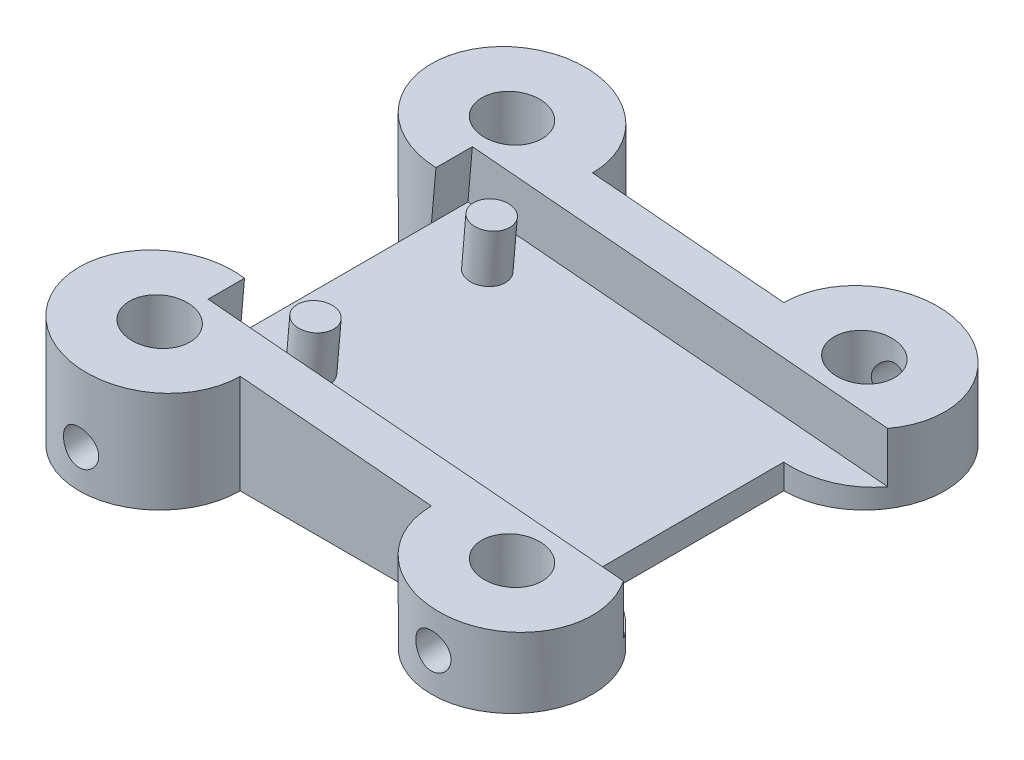
SolidWorks part; units mm, degrees
ref_plane "Front Plane" through (0, 0, 0) normal (0, 0, 1) x (1, 0, 0)
ref_plane "Top Plane" through (0, 0, 0) normal (0, 1, 0) x (1, 0, 0)
ref_plane "Right Plane" through (0, 0, 0) normal (1, 0, 0) x (0, 0, -1)
sketch "Sketch1" plane through (0, 0, 0) normal (0, 1, 0) x (1, 0, 0)
  line L0 (14, 28) -> (14, 0) construction
  line L1 (0, 0) -> (28, 0)
  line L2 (0, 0) -> (0, 28)
  line L3 (0, 28) -> (28, 28)
  line L4 (28, 0) -> (28, 28)
  line L5 (0, 14) -> (28, 14) construction
  point P9 (14, 14)
  dimension "D1" = 28
extrude "Boss-Extrude1" add sketch "Sketch1" along normal blind 8.4497
sketch "Sketch2" plane through (0, 0, 0) normal (0, 0, 1) x (1, 0, 0)
  line L0 (0, 8.4497) -> (28, 6)
  line L1 (0, 8.4497) -> (28, 8.4497) construction
  line L2 (28, 8.4497) -> (28, 0) construction
  line L3 (0, 8.4497) -> (28, 8.4497)
  line L4 (28, 8.4497) -> (28, 6)
  dimension "D2" = 6
  dimension "D3" = 5
extrude "Cut-Extrude1" cut sketch "Sketch2" against normal through all
sketch "Sketch3" plane through (0.7336, 8.3855, 0) normal (0.0872, 0.9962, 0) x (0.9962, -0.0872, 0)
  line L0 (-0.7364, 28) -> (-0.7364, 0) construction
  line L1 (-0.7364, 3.5) -> (49.2636, 3.5)
  line L2 (-0.7364, 3.5) -> (-0.7364, 24.5)
  line L3 (-0.7364, 24.5) -> (49.2636, 24.5)
  line L4 (49.2636, 3.5) -> (49.2636, 24.5)
  point P9 (-0.7364, 14)
  point P10 (-0.7364, 14)
  dimension "D1" = 21
  dimension "D2" = 50
extrude "Cut-Extrude2" cut sketch "Sketch3" against normal blind 4
ref_plane "Plane1" through (0, 8.4497, 0) normal (0, 1, 0) x (1, 0, 0)
sketch "Sketch11" plane through (0.385, 4.4007, 0) normal (0.0872, 0.9962, 0) x (0.9962, -0.0872, 0)
  line L0 (27.7205, 24.5) -> (-0.3865, 24.5) construction
  line L1 (27.7205, 24.5) -> (27.7205, 3.5) construction
  line L2 (-0.3865, 3.5) -> (27.7205, 3.5) construction
  line L3 (27.7205, 24.5) -> (-0.3865, 24.5) construction
  line L4 (27.7205, 24.5) -> (27.7205, 3.5) construction
  line L5 (-0.3865, 3.5) -> (27.7205, 3.5) construction
  line L6 (13.667, 3) -> (13.667, 50003) construction
  line L7 (24.633, 14) -> (-49975.367, 14) construction
  circle A2 centre (4.667, 21) radius 1.45
  circle A3 centre (4.667, 7) radius 1.45
  point P6 (13.667, 3.5)
  point P9 (27.7205, 14)
  dimension "D4" = 2.9
  dimension "D5" = 9
  dimension "D6" = 7
extrude "Boss-Extrude2" add sketch "Sketch11" along normal blind 4
sketch "Sketch12" plane through (0, 8.4497, 0) normal (0, 1, 0) x (1, 0, 0)
  line L0 (0, 3.5) -> (0, 24.5) construction
  line L1 (0, 3.5) -> (28, 3.5) construction
  line L2 (0, 3.5) -> (0, 24.5) construction
  line L3 (0, 3.5) -> (28, 3.5) construction
  line L4 (0, 14) -> (50000, 14) construction
  line L5 (14, 4) -> (14, 50004) construction
  circle A0 centre (14, 14) radius 7
  point P7 (0, 14)
  point P10 (14, 3.5)
  dimension "D1" = 14
sketch "Sketch13" plane through (0, 0, 0) normal (0, -1, 0) x (1, 0, 0)
  line L0 (0, 0) -> (28, 0) construction
  line L1 (28, 0) -> (28, -28) construction
  line L2 (28, -28) -> (0, -28) construction
  line L3 (0, -28) -> (0, 0) construction
  line L4 (0, 0) -> (28, 0) construction
  line L5 (28, 0) -> (28, -28) construction
  line L6 (28, -28) -> (0, -28) construction
  line L7 (0, -28) -> (0, 0) construction
  line L8 (0, -14) -> (28, -14) construction
  line L9 (14, -28) -> (14, 0) construction
  circle A0 centre (0, 0) radius 2.4
  circle A1 centre (28, 0) radius 2.4
  circle A2 centre (28, -28) radius 2.4
  circle A3 centre (0, -28) radius 2.4
  dimension "D1" = 4.8
  dimension "D2" = 2
  dimension "D3" = 2
extrude "Cut-Extrude5" cut sketch "Sketch13" against normal through all
sketch "Sketch14" plane through (0, 0, 0) normal (0, -1, 0) x (1, 0, 0)
  line L0 (28, -3.5) -> (28, -2.4) construction
  line L1 (2.4, -28) -> (25.6, -28) construction
  line L2 (0, -3.5) -> (0, -24.5) construction
  circle A0 centre (0, 0) radius 2.4 construction
  circle A1 centre (0, 0) radius 2.4 construction
  circle A2 centre (0, 0) radius 6.4
  circle A3 centre (0, 0) radius 2.4
  circle A4 centre (28, 0) radius 2.4
  circle A5 centre (28, 0) radius 6.4
  circle A6 centre (28, -28) radius 2.4
  circle A7 centre (28, -28) radius 6.4
  circle A8 centre (0, -28) radius 2.4
  circle A9 centre (0, -28) radius 6.4
  dimension "D1" = 4
  dimension "D4" = 4.8
  dimension "D2" = 2
  dimension "D3" = 2
extrude "Boss-Extrude3" add sketch "Sketch14" against normal up to surface (8.4497 mm away)
sketch "Sketch15" plane through (0, 0, -28) normal (0, 0, -1) x (-1, 0, 0)
  line L0 (-21.6, 0) -> (-6.4, 0) construction
  line L1 (-21.9, 0) -> (-0.9, 0) construction
  line L4 (-14, 7.2248) -> (-14, 0) construction
  line L5 (-6.4, 7.8898) -> (-21.6, 6.5599) construction
  circle A0 centre (-28, 3) radius 1.4
  circle A1 centre (0, 3) radius 1.4
  point P4 (-28, 0)
  dimension "D1" = 2.8
  dimension "D2" = 3
extrude "Cut-Extrude6" cut sketch "Sketch15" along normal through all
sketch "Sketch16" plane through (0, 0, 0) normal (0, 0, 1) x (1, 0, 0)
  circle A0 centre (0, 3) radius 1.4 construction
  circle A1 centre (28, 3) radius 1.4 construction
  circle A2 centre (0, 3) radius 1.4
  circle A3 centre (28, 3) radius 1.4
extrude "Cut-Extrude7" cut sketch "Sketch16" along normal through all
sketch "Sketch18" plane through (0.7336, 8.3855, 0) normal (0.0872, 0.9962, 0) x (0.9962, -0.0872, 0)
  line L5 (-0.7364, 3.5) -> (27.157, 3.5) construction
  line L8 (4.6422, 3.5) -> (21.9919, 3.5) construction
  line L9 (4.6422, 3.5) -> (21.9919, 3.5) construction
  line L22 (4.9922, 24.5) -> (-0.3865, 24.5)
  line L37 (6.9919, 3.5) -> (36.9919, 3.5)
  line L38 (6.9919, 3.5) -> (6.9919, 24.5)
  line L39 (6.9919, 24.5) -> (36.9919, 24.5)
  line L40 (36.9919, 3.5) -> (36.9919, 24.5)
  line L42 (-0.3865, 24.5) -> (-0.3865, 21.6)
  line L46 (-0.3865, 6.4) -> (-0.3865, 3.5)
  line L47 (-0.3865, 3.5) -> (4.9922, 3.5)
  line L49 (4.6422, 24.5) -> (21.9919, 24.5) construction
  ellipse E1 centre (-0.3865, 28) end of major axis (6.038, 28) minor radius 6.4 (-0.3865, 21.6) -> (4.9922, 24.5) ccw construction
  ellipse E2 centre (-0.3865, 28) end of major axis (6.038, 28) minor radius 6.4 (-0.3865, 21.6) -> (4.9922, 24.5) ccw
  ellipse E3 centre (-0.3865, 0) end of major axis (6.038, 0) minor radius 6.4 (4.9922, 3.5) -> (-0.3865, 6.4) ccw construction
  ellipse E4 centre (-0.3865, 0) end of major axis (6.038, 0) minor radius 6.4 (4.9922, 3.5) -> (-0.3865, 6.4) ccw
  point P7 (21.9919, 3.5)
  dimension "D1" = 30
extrude "Cut-Extrude8" cut sketch "Sketch18" against normal up to surface (4 mm away) up to face at (6.4787, 3.8676, -21)
equation "\"TrackLength\"= 150"
equation "\"MarbleWidth\"= 13"
equation "\"MarbleTrackWidth\"= \"MarbleWidth\" - 1"
equation "\"TrackWidth\"= \"MarbleTrackWidth\" + ( 2 * 4 )"
equation "\"MarbleTrackLength\"= \"TrackLength\" - ( 2 * 8 )"
equation "\"MountWidth\"= \"TrackWidth\" + 8"
equation "\"D1@Sketch1\"=\"MountWidth\""
equation "\"D1@Boss-Extrude1\"=\"RampHeight\""
equation "\"RampDepth\"=6"
equation "\"RampAngle\"= 5"
equation "\"RampHeight\"= ( \"MountWidth\" * tan ( \"RampAngle\" ) ) + \"RampDepth\""
equation "\"D1@Sketch3\"=\"TrackWidth\" + 1"
equation "\"MountWidth\"= \"TrackWidth\" + 10"
equation "\"MountLength\"=66.6651"
